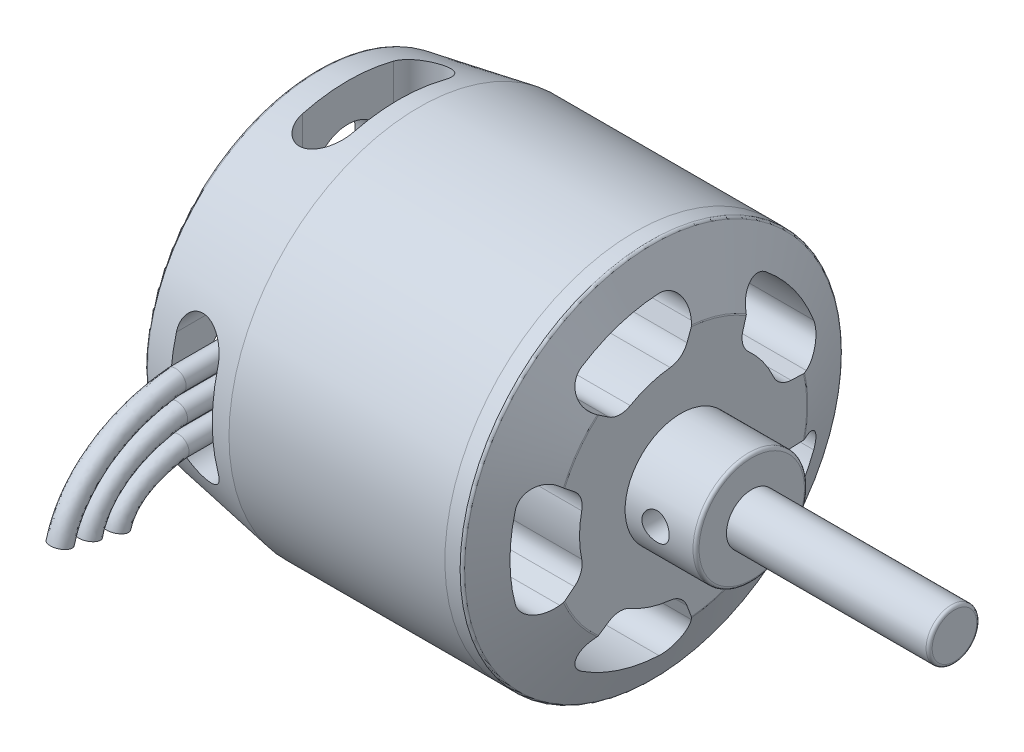
SolidWorks part; units mm, degrees
ref_plane "Front" through (0, 0, 0) normal (0, 0, 1) x (1, 0, 0)
ref_plane "Top" through (0, 0, 0) normal (0, 1, 0) x (1, 0, 0)
ref_plane "Right" through (0, 0, 0) normal (1, 0, 0) x (0, 0, -1)
sketch "Sketch1" plane through (0, 0, 0) normal (0, 0, 1) x (1, 0, 0)
  line L0 (0, 0) -> (-64, 0) construction
  line L1 (0, 0) -> (0, 4.75)
  line L2 (0, 4.75) -> (5, 4.75)
  line L3 (5, 4.75) -> (5, 17)
  line L4 (5, 17) -> (15, 18.75)
  line L5 (15, 18.75) -> (38, 18.75)
  line L6 (38, 18.75) -> (40.84, 12.5)
  line L7 (40.84, 12.5) -> (40.84, 5.5)
  line L8 (40.84, 5.5) -> (47.84, 5.5)
  line L9 (47.84, 5.5) -> (47.84, 2.5)
  line L10 (47.84, 2.5) -> (67.84, 2.5)
  line L11 (67.84, 2.5) -> (67.84, 0)
  line L12 (67.84, 0) -> (0, 0)
  dimension "D1" = 5
  dimension "D2" = 11
  dimension "D3" = 25
  dimension "D4" = 20
  dimension "D5" = 7
  dimension "D6" = 23
  dimension "D7" = 9.5
  dimension "D8" = 5
  dimension "D9" = 10
  dimension "D10" = 35.84
  dimension "D11" = 34
  dimension "D12" = 37.5
revolve "Revolve1" add sketch "Sketch1" angle 360 about L0
fillet "Fillet1" radius 0.3 1 edges at (47.84, 0, -5.5)
sketch "Sketch2" plane through (40.84, 0, 0) normal (1, 0, 0) x (0, 0, -1)
  line L0 (0, 0) -> (-18.75, 0) construction
  line L1 (-10.5003, 4.0536) -> (-11.7965, 5.0775)
  line L3 (-10.5003, -4.0536) -> (-11.7965, -5.0775)
  line L4 (-15.5, 0) -> (-10, 0)
  line L5 (0.6104, 11.239) -> (1.1837, 12.7881)
  line L6 (-7.1, 8.7337) -> (-8.4743, 9.6501)
  line L7 (10.8776, 2.8925) -> (12.528, 2.826)
  line L8 (6.1123, 9.4513) -> (6.5591, 11.0416)
  line L9 (6.1123, -9.4513) -> (6.5591, -11.0416)
  line L10 (10.8776, -2.8925) -> (12.528, -2.826)
  line L11 (-7.1, -8.7337) -> (-8.4743, -9.6501)
  line L12 (0.6104, -11.239) -> (1.1837, -12.7881)
  arc A0 (-9.7834, -2.0702) -> (-10.5003, -4.0536) centre (-11.74, -2.4842) cw
  circle A1 centre (0, 0) radius 18.75 construction
  arc A2 (-14.9675, 4.0278) -> (-14.9675, -4.0278) centre (0, 0) ccw
  arc A3 (-9.7834, 2.0702) -> (-9.7834, -2.0702) centre (0, 0) ccw
  arc A6 (-9.7834, 2.0702) -> (-10.5003, 4.0536) centre (-11.74, 2.4842) ccw
  arc A7 (-11.7965, 5.0775) -> (-14.9675, 4.0278) centre (-13.0362, 3.5081) ccw
  arc A8 (-11.7965, -5.0775) -> (-14.9675, -4.0278) centre (-13.0362, -3.5081) cw
  arc A9 (-0.7945, 15.4796) -> (-8.4559, 12.9903) centre (0, 0) ccw
  arc A10 (1.1837, 12.7881) -> (-0.7945, 15.4796) centre (-0.692, 13.4823) ccw
  arc A11 (-1.0544, 9.9443) -> (0.6104, 11.239) centre (-1.2653, 11.9331) ccw
  arc A12 (-4.9921, 8.6648) -> (-7.1, 8.7337) centre (-5.9905, 10.3978) cw
  arc A13 (-8.4743, 9.6501) -> (-8.4559, 12.9903) centre (-7.3648, 11.3141) cw
  arc A14 (-1.0544, 9.9443) -> (-4.9921, 8.6648) centre (0, 0) ccw
  arc A15 (14.4765, 5.5391) -> (9.7415, 12.0563) centre (0, 0) ccw
  arc A16 (12.528, 2.826) -> (14.4765, 5.5391) centre (12.6085, 4.8244) ccw
  arc A17 (9.1317, 4.0757) -> (10.8776, 2.8925) centre (10.9581, 4.8909) ccw
  arc A18 (6.6981, 7.4253) -> (6.1123, 9.4513) centre (8.0377, 8.9104) cw
  arc A19 (6.5591, 11.0416) -> (9.7415, 12.0563) centre (8.4845, 10.5006) cw
  arc A20 (9.1317, 4.0757) -> (6.6981, 7.4253) centre (0, 0) ccw
  arc A21 (9.7415, -12.0563) -> (14.4765, -5.5391) centre (0, 0) ccw
  arc A22 (6.5591, -11.0416) -> (9.7415, -12.0563) centre (8.4845, -10.5006) ccw
  arc A23 (6.6981, -7.4253) -> (6.1123, -9.4513) centre (8.0377, -8.9104) ccw
  arc A24 (9.1317, -4.0757) -> (10.8776, -2.8925) centre (10.9581, -4.8909) cw
  arc A25 (12.528, -2.826) -> (14.4765, -5.5391) centre (12.6085, -4.8244) cw
  arc A26 (6.6981, -7.4253) -> (9.1317, -4.0757) centre (0, 0) ccw
  arc A27 (-8.4559, -12.9903) -> (-0.7945, -15.4796) centre (0, 0) ccw
  arc A28 (-8.4743, -9.6501) -> (-8.4559, -12.9903) centre (-7.3648, -11.3141) ccw
  arc A29 (-4.9921, -8.6648) -> (-7.1, -8.7337) centre (-5.9905, -10.3978) ccw
  arc A30 (-1.0544, -9.9443) -> (0.6104, -11.239) centre (-1.2653, -11.9331) cw
  arc A31 (1.1837, -12.7881) -> (-0.7945, -15.4796) centre (-0.692, -13.4823) cw
  arc A32 (-4.9921, -8.6648) -> (-1.0544, -9.9443) centre (0, 0) ccw
  point P14 (-13.9421, -6.7725)
  point P21 (-13.9421, 6.7725)
  circle M15 centre (0, 0) radius 12.5
  dimension "D1" = 31
  dimension "D2" = 20
extrude "Cut-Extrude1" cut sketch "Sketch2" against normal blind 10 contours A25 L10 L9 A22 A21 M15 | A26 A23 L9 L10 A24 M15 | A31 L12 L11 A28 A27 M15 | A32 A29 L11 L12 A30 M15 | A8 L3 L4 A2 M15 | A3 L4 L3 A0 M15 | L1 A7 A2 L4 M15 | A3 A6 L1 L4 M15 | A13 L6 L5 A10 A9 M15 | A14 A11 L5 L6 A12 M15 | A20 A17 L7 L8 A18 M15 | A19 L8 L7 A16 A15 M15
ref_plane "Plane1" through (0, 0, 18.75) normal (0, 0, 1) x (1, 0, 0)
sketch "Sketch3" plane through (0, 0, 18.75) normal (0, 0, 1) x (1, 0, 0)
  line L0 (15, 0) -> (5, 0) construction
  line L1 (15, 18.75) -> (15, -18.75) construction
  line L2 (5, 4.75) -> (5, -4.75) construction
  line L3 (10.5, -4.5) -> (10.5, 4.5) construction
  line L4 (8, -4.5) -> (8, 4.5)
  line L5 (13, -4.5) -> (13, 4.5)
  line L6 (5, 17) -> (5, -17) construction
  arc A0 (8, -4.5) -> (13, -4.5) centre (10.5, -4.5) ccw
  arc A1 (13, 4.5) -> (8, 4.5) centre (10.5, 4.5) ccw
  point P8 (10.5, 0)
  point P13 (10.5, -7)
  point P16 (10.5, 7)
  dimension "D1" = 5
  dimension "D2" = 3
  dimension "D3" = 14
extrude "Cut-Extrude2" cut sketch "Sketch3" against normal blind 10
pattern_circular "CirPattern1" count 4 over 360 about axis through (0, 0, 0) along (1, 0, 0) of "Cut-Extrude2"
sketch "Sketch4" plane through (0, 0, 0) normal (-1, 0, 0) x (0, 0, 1)
  circle A0 centre (0, 0) radius 2.5
  dimension "D1" = 5
split line "Split Line1"
fillet "Fillet2" radius 0.3 8 edges at (40.84, -11.8882, -3.8627) (40.84, -7.3473, 10.1127) (40.84, 7.3473, 10.1127) (40.84, 11.8882, -3.8627) (40.84, 0, -12.5) (38, 0, -18.75) (5, 0, -17) (0, 0, -4.75)
sketch "Sketch5" plane through (0, 0, 18.75) normal (0, 0, 1) x (1, 0, 0)
  line L0 (0, 0) -> (5.2483, 0) construction
  line L1 (0, 4.45) -> (0, -4.45) construction
  line L2 (5.2483, -17.0435) -> (5.2483, 17.0435) construction
  line L3 (40.84, 0) -> (46.84, 0) construction
  line L4 (40.84, -2.0702) -> (40.84, 2.0702) construction
  line L6 (40.84, -5.5) -> (40.84, 5.5) construction
  circle A0 centre (2.6241, 0) radius 1.35
  circle A1 centre (43.84, 0) radius 1.35
  dimension "D1" = 2.7
  dimension "D2" = 3
extrude "Cut-Extrude3" cut sketch "Sketch5" against normal offset from surface (16 mm away) 2 up to face at (0.3, 0, 4.75) offset beyond the face yes
sketch "Sketch6" plane through (5, 0, 0) normal (-1, 0, 0) x (0, 0, 1)
  line L0 (0, 0) -> (-10.3, 0) construction
  line L1 (2.4749, 7.8251) -> (7.8251, 2.4749) construction
  line L2 (0, 0) -> (-19.91, 19.91) construction
  line L3 (0, 0) -> (-8.85, 8.85) construction
  line L4 (0, 0) -> (8.85, 8.85) construction
  line L5 (-7.625, 8.85) -> (7.625, 8.85) construction
  circle A0 centre (0, 0) radius 10.3 construction
  circle A1 centre (-10.3, 0) radius 3.5
  circle A2 centre (0, 10.3) radius 3.5
  circle A3 centre (10.3, 0) radius 3.5
  circle A4 centre (0, -10.3) radius 3.5
  circle A5 centre (0, 0) radius 12.5158 construction
  circle A6 centre (-8.85, 8.85) radius 1.225
  circle A7 centre (8.85, 8.85) radius 1.225
  circle A8 centre (8.85, -8.85) radius 1.225
  circle A9 centre (-8.85, -8.85) radius 1.225
  point P3 (2.4749, 7.8251)
  point P5 (-6.8, 0)
  point P6 (6.8, 0)
  point P7 (7.8251, 2.4749)
  point P33 (-8.85, 8.85)
  dimension "D1" = 13.6
  dimension "D3" = 7
  dimension "D4" = 90
  dimension "D6" = 2.45
  dimension "D7" = 15.25
  dimension "D2" = 4
  dimension "D5" = 4
extrude "Cut-Extrude4" cut sketch "Sketch6" against normal up to surface (8 mm away) up to face at (13, 0, -13.4353)
chamfer "Chamfer1" distance 0.2 angle 45 8 edges at (5, 0, 13.8) (5, 8.85, 10.075) (5, 10.3, 3.5) (5, -8.85, 10.075) (5, -10.3, 3.5) (5, -8.85, -7.625) (5, 8.85, -7.625) (5, 0, -6.8)
fillet "Fillet3" radius 0.3 1 edges at (67.84, 0, -2.5)
sketch "Sketch7" plane through (0, 0, 18.75) normal (0, 0, 1) x (1, 0, 0)
  line L0 (36.3068, 24.3404) -> (36.3068, -27.9982)
  line L1 (37.8068, 18.75) -> (37.8068, -18.75) construction
  dimension "D1" = 1.5
split line "Split Line2"
ref_plane "Plane2" through (0, 0, 13.8) normal (0, 0, 1) x (1, 0, 0)
sketch "Sketch9" plane through (0, 0, 13.8) normal (0, 0, 1) x (1, 0, 0)
  line L0 (10.4455, 0) -> (0, 0) construction
  circle A0 centre (10.4455, 2.876) radius 1
  circle A1 centre (10.4455, 0) radius 1
  circle A2 centre (10.4455, -2.876) radius 1
  dimension "D1" = 2
ref_plane "Plane3" through (10.4455, 0, 0) normal (1, 0, 0) x (0, 0, -1)
sketch "Sketch10" plane through (10.4455, 0, 0) normal (1, 0, 0) x (0, 0, -1)
  line L0 (-13.8, 0) -> (-19.2771, 0)
  spline S0 degree 3 poles (-19.2771, 0) (-22.9011, -0.3453) (-27.0603, -2.1577) (-28.0775, -6.0781) knots 0 0 0 0 1 1 1 1
sweep "Sweep1" add profiles "Sketch9" path "Sketch10"
